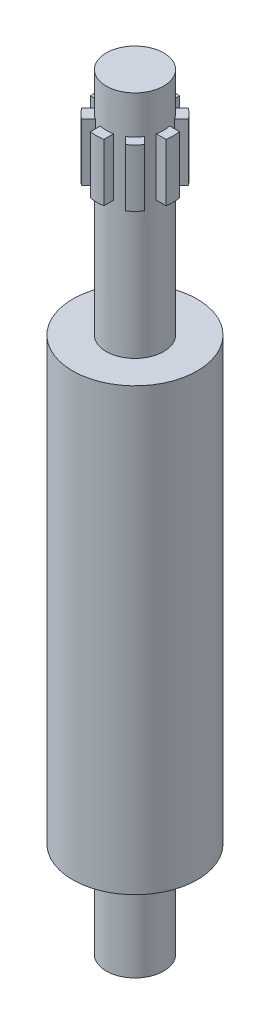
SolidWorks part; units mm, degrees
ref_plane "Front Plane" through (0, 0, 0) normal (0, 0, 1) x (1, 0, 0)
ref_plane "Top Plane" through (0, 0, 0) normal (0, 1, 0) x (1, 0, 0)
ref_plane "Right Plane" through (0, 0, 0) normal (1, 0, 0) x (0, 0, -1)
sketch "Sketch1" plane through (0, 0, 0) normal (0, 1, 0) x (1, 0, 0)
  circle A0 centre (0, 0) radius 32.5
  dimension "D1" = 65
extrude "Boss-Extrude1" add sketch "Sketch1" along normal blind 230
sketch "Sketch2" plane through (0, 230, 0) normal (0, 1, 0) x (1, 0, 0)
  circle A0 centre (0, 0) radius 15
  dimension "D1" = 30
extrude "Boss-Extrude2" add sketch "Sketch2" along normal blind 100
sketch "Sketch3" plane through (0, 0, 0) normal (0, -1, 0) x (1, 0, 0)
  circle A0 centre (0, 0) radius 15
  dimension "D1" = 30
extrude "Boss-Extrude3" add sketch "Sketch3" along normal blind 50
sketch "Sketch4" plane through (0, 330, 0) normal (0, 1, 0) x (1, 0, 0)
  line L0 (-3.5, 19.6914) -> (-3.5, 14.586)
  line L1 (0, 0) -> (0, 35.4521) construction
  line L2 (3.5, 14.586) -> (3.5, 19.6914)
  line L3 (11.449, 16.3988) -> (7.839, 12.7887)
  line L4 (12.7887, 7.839) -> (16.3988, 11.449)
  line L5 (19.6914, 3.5) -> (14.586, 3.5)
  line L6 (14.586, -3.5) -> (19.6914, -3.5)
  line L7 (16.3988, -11.449) -> (12.7887, -7.839)
  line L8 (7.839, -12.7887) -> (11.449, -16.3988)
  line L9 (3.5, -19.6914) -> (3.5, -14.586)
  line L10 (-3.5, -14.586) -> (-3.5, -19.6914)
  line L11 (-11.449, -16.3988) -> (-7.839, -12.7887)
  line L12 (-12.7887, -7.839) -> (-16.3988, -11.449)
  line L13 (-19.6914, -3.5) -> (-14.586, -3.5)
  line L14 (-14.586, 3.5) -> (-19.6914, 3.5)
  line L15 (-16.3988, 11.449) -> (-12.7887, 7.839)
  line L16 (-7.839, 12.7887) -> (-11.449, 16.3988)
  arc A0 (-3.5, 14.586) -> (-7.839, 12.7887) centre (0, 0) ccw
  arc A1 (-19.6914, 3.5) -> (-19.6914, -3.5) centre (0, 0) ccw
  arc A2 (-11.449, 16.3988) -> (-16.3988, 11.449) centre (0, 0) ccw
  arc A3 (3.5, 19.6914) -> (-3.5, 19.6914) centre (0, 0) ccw
  arc A4 (16.3988, 11.449) -> (11.449, 16.3988) centre (0, 0) ccw
  arc A5 (19.6914, -3.5) -> (19.6914, 3.5) centre (0, 0) ccw
  arc A6 (11.449, -16.3988) -> (16.3988, -11.449) centre (0, 0) ccw
  arc A7 (-3.5, -19.6914) -> (3.5, -19.6914) centre (0, 0) ccw
  arc A8 (-16.3988, -11.449) -> (-11.449, -16.3988) centre (0, 0) ccw
  arc A9 (-14.586, -3.5) -> (-12.7887, -7.839) centre (0, 0) ccw
  arc A10 (-12.7887, 7.839) -> (-14.586, 3.5) centre (0, 0) ccw
  arc A11 (7.839, 12.7887) -> (3.5, 14.586) centre (0, 0) ccw
  arc A12 (14.586, 3.5) -> (12.7887, 7.839) centre (0, 0) ccw
  arc A13 (12.7887, -7.839) -> (14.586, -3.5) centre (0, 0) ccw
  arc A14 (3.5, -14.586) -> (7.839, -12.7887) centre (0, 0) ccw
  arc A15 (-7.839, -12.7887) -> (-3.5, -14.586) centre (0, 0) ccw
  point P39 (0, 0)
  dimension "D1" = 30
  dimension "D2" = 40
  dimension "D3" = 7
  dimension "D4" = 8
extrude "Boss-Extrude4" add sketch "Sketch4" against normal blind 30
sketch "Sketch5" plane through (0, 330, 0) normal (0, 1, 0) x (1, 0, 0)
  circle A0 centre (0, 0) radius 15
extrude "Boss-Extrude5" add sketch "Sketch5" along normal blind 20
